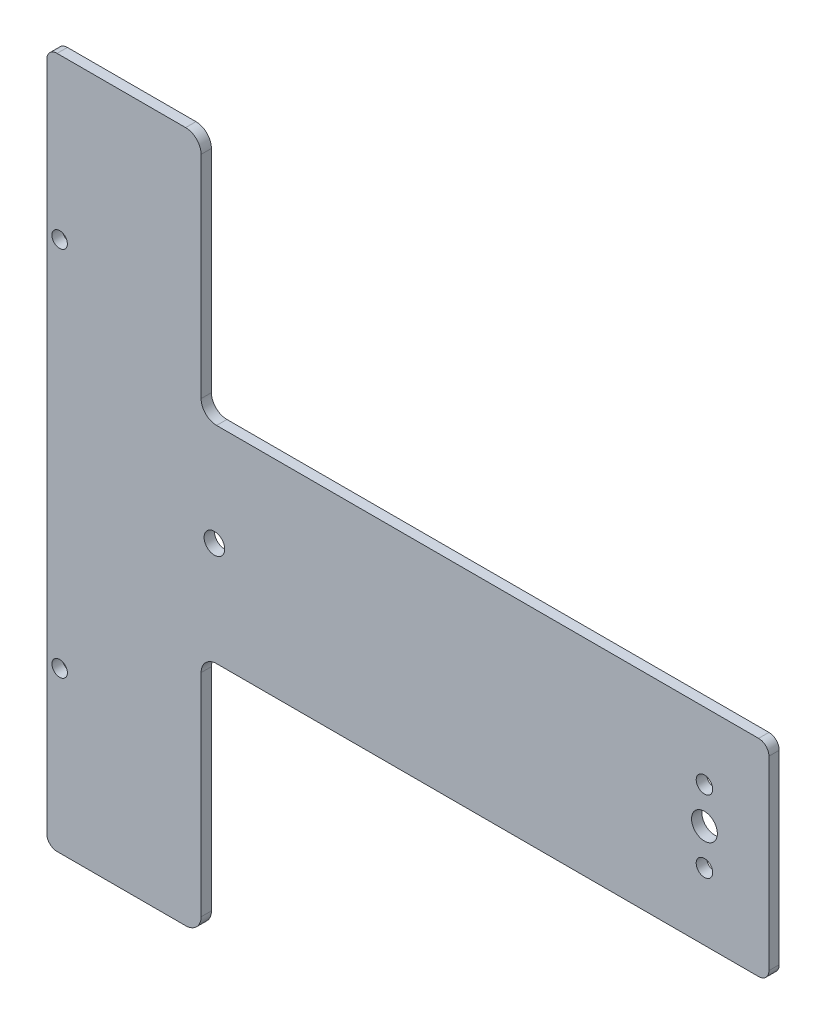
SolidWorks part; units mm, degrees
ref_plane "前视基准面" through (0, 0, 0) normal (0, 0, 1) x (1, 0, 0)
ref_plane "上视基准面" through (0, 0, 0) normal (0, 1, 0) x (1, 0, 0)
ref_plane "右视基准面" through (0, 0, 0) normal (1, 0, 0) x (0, 0, -1)
other "Configuration Table"
sketch3d "3D草图1"
  point P0 (0, 0, 45.6561)
  point P1 (10, 0, 45.6561)
  point P2 (0, 10, 45.6561)
ref_plane "基准面1" through (0, 0, 45.6561) normal (0, 0, 1) x (1, 0, 0)
sketch "草图1" plane through (0, 0, 45.6561) normal (0, 0, 1) x (1, 0, 0)
  line L0 (82.0784, 65) -> (82.0784, -65)
  line L1 (84.0784, -67) -> (109, -67)
  line L2 (112, -64) -> (112, -23)
  line L3 (115, -20) -> (220.0784, -20)
  line L4 (222.0784, -18) -> (222.0784, 18)
  line L5 (220.0784, 20) -> (115, 20)
  line L6 (112, 23) -> (112, 64)
  line L7 (109, 67) -> (84.0784, 67)
  arc A0 (82.0784, -65) -> (84.0784, -67) centre (84.0784, -65) ccw
  arc A1 (109, -67) -> (112, -64) centre (109, -64) ccw
  arc A2 (112, -23) -> (115, -20) centre (115, -23) cw
  arc A3 (220.0784, -20) -> (222.0784, -18) centre (220.0784, -18) ccw
  arc A4 (222.0784, 18) -> (220.0784, 20) centre (220.0784, 18) ccw
  arc A5 (115, 20) -> (112, 23) centre (115, 23) cw
  arc A6 (112, 64) -> (109, 67) centre (109, 64) ccw
  arc A7 (84.0784, 67) -> (82.0784, 65) centre (84.0784, 65) ccw
extrude "凸台-拉伸1" add sketch "草图1" along normal blind 2
sketch3d "3D草图2"
  point P0 (0, 0, 45.6561)
  point P1 (10, 0, 45.6561)
  point P2 (0, 10, 45.6561)
ref_plane "基准面2" through (0, 0, 45.6561) normal (0, 0, 1) x (1, 0, 0)
sketch "草图2" plane through (0, 0, 45.6561) normal (0, 0, 1) x (1, 0, 0)
  circle A0 centre (209.5784, 0) radius 2.5
  circle A1 centre (114.5784, 0) radius 2
  circle A2 centre (84.5784, -36) radius 1.5
  circle A3 centre (84.5784, 36) radius 1.5
extrude "切除-拉伸1" cut sketch "草图2" along normal blind 2
sketch3d "3D草图3"
  point P0 (0, 0, 45.6561)
  point P1 (10, 0, 45.6561)
  point P2 (0, 10, 45.6561)
ref_plane "基准面3" through (0, 0, 45.6561) normal (0, 0, 1) x (1, 0, 0)
sketch "草图3" plane through (0, 0, 45.6561) normal (0, 0, 1) x (1, 0, 0)
  circle A0 centre (209.5786, -7) radius 1.6
  circle A1 centre (209.5786, 7) radius 1.6
extrude "切除-拉伸2" cut sketch "草图3" along normal blind 2
